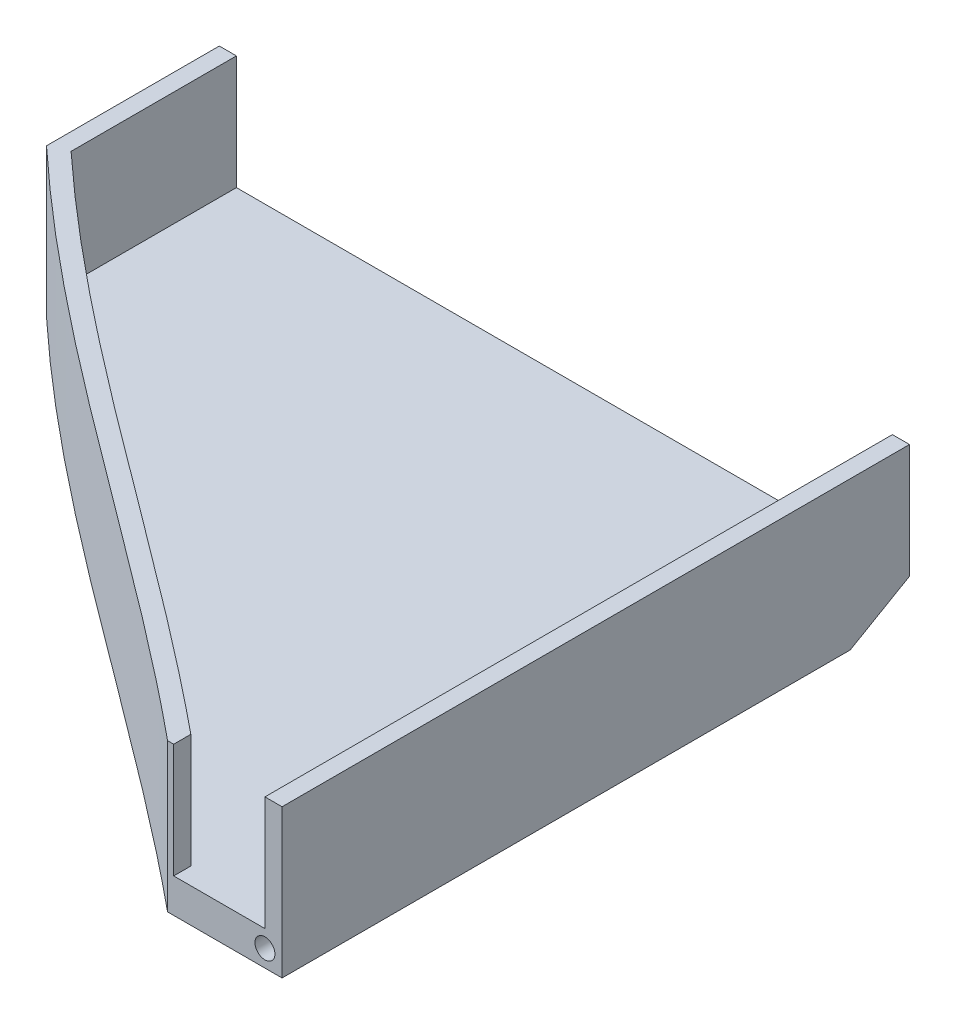
SolidWorks part; units mm, degrees
ref_plane "Front Plane" through (0, 0, 0) normal (0, 0, 1) x (1, 0, 0)
ref_plane "Top Plane" through (0, 0, 0) normal (0, 1, 0) x (1, 0, 0)
ref_plane "Right Plane" through (0, 0, 0) normal (1, 0, 0) x (0, 0, -1)
sketch "Sketch1" plane through (0, 0, 0) normal (0, 1, 0) x (1, 0, 0)
  line L0 (0, 0) -> (-121, 0)
  line L1 (0, 0) -> (0, -110)
  line L2 (-121, 0) -> (-121, -30.2986)
  line L3 (-20.07, -110) -> (0, -110)
  spline S0 degree 3 poles (-121, -30.2986) (-89.5585, -59.6551) (-53.1894, -82.7397) (-20.07, -110) knots 0 0 0 0 1 1 1 1
  point P6 (-121, -14.297)
  point P8 (-20.498, -110)
  dimension "D1" = 121
  dimension "D2" = 110
  dimension "D3" = 38.023
  dimension "D4" = 40
  dimension "D5" = 20.07
  dimension "D6" = 31.7014
  dimension "D7" = 30
  dimension "D8" = 18
extrude "Boss-Extrude1" add sketch "Sketch1" along normal blind 6
sketch "Sketch2" plane through (0, 0, 0) normal (0, 0, -1) x (-1, 0, 0)
  line L0 (3, 4.75) -> (3, 6) construction
  line L1 (0, 6) -> (121, 6) construction
  line L2 (3, 1.25) -> (3, 0) construction
  line L3 (0, 0) -> (121, 0) construction
  line L4 (1.25, 3) -> (0, 3) construction
  line L5 (0, 6) -> (0, 0) construction
  circle A0 centre (3, 3) radius 1.75
  dimension "D1" = 3.5
extrude "Cut-Extrude1" cut sketch "Sketch2" against normal through all both and the other way through all
sketch "Sketch3" plane through (0, 6, 0) normal (0, 1, 0) x (1, 0, 0)
  line L4 (-118, -3) -> (-118, 0)
  line L5 (0, 0) -> (-121, 0) construction
  line L6 (-3, -3) -> (-3, 0)
  line L7 (-18.9959, -107) -> (-18.9959, -110)
  line L8 (-3, -107) -> (-3, -3)
  line L9 (-3, -3) -> (-118, -3)
  line L10 (-118, -3) -> (-118, -28.9919)
  line L11 (-18.9959, -107) -> (-3, -107)
  line L12 (-3, -107) -> (-3, -3)
  line L14 (-118, -3) -> (-118, -28.9919)
  line L16 (-20.07, -110) -> (0, -110) construction
  line L17 (-3, -107) -> (-3, -110)
  line L18 (-118, 0) -> (-121, 0)
  line L19 (-3, -110) -> (0, -110)
  line L22 (0, -110) -> (0, 0)
  line L23 (0, 0) -> (-121, 0)
  line L24 (-121, 0) -> (-121, -30.2986)
  line L25 (-20.07, -110) -> (0, -110)
  line L26 (0, -110) -> (0, 0)
  line L27 (0, 0) -> (-3, 0)
  line L28 (-121, 0) -> (-121, -30.2986)
  line L29 (-20.07, -110) -> (-18.9959, -110)
  spline S2 degree 3 poles (649.1302, 1789.6761) (-350.2754, 298.2092) (-258.2349, 82.2153) (-85.8796, -56.0777) (-77.5136, -62.4365) (113.5898, -205.4544) (318.6219, -312.955) (-660.7218, -1970.0693) knots -4.756868 -4.756868 -4.756868 -4.756868 0.25 0.25 0.5 0.5 5.928718 5.928718 5.928718 5.928718 only from (-118, -28.9919) to (-18.9959, -107)
  spline S3 degree 3 poles (-118, -28.9919) (-110.2898, -36.1372) (-102.273, -42.9241) (-85.8796, -56.0777) (-77.5136, -62.4365) (-52.2742, -81.3252) (-35.2584, -93.6698) (-18.9959, -107) knots 0 0 0 0 0.25 0.25 0.5 0.5 1 1 1 1
  spline S4 degree 3 poles (571.5988, 1819.0788) (-1410.1109, -1437.193) (1283.6504, 1277.4641) (-683.5692, -1965.4922) knots -4.631393 -4.631393 -4.631393 -4.631393 5.820366 5.820366 5.820366 5.820366 only from (-121, -30.2986) to (-20.07, -110)
  spline S5 degree 3 poles (-121, -30.2986) (-89.5585, -59.6551) (-53.1894, -82.7397) (-20.07, -110) knots 0 0 0 0 1 1 1 1
  dimension "D2" = 0
  dimension "D1" = 3
extrude "Boss-Extrude2" add sketch "Sketch3" along normal blind 20
ref_plane "Plane1" through (0, 4.5, 2.5981) normal (0, -0.866, -0.5) x (-1, 0, 0)
sketch "Sketch4" plane through (0, 4.5, 2.5981) normal (0, -0.866, -0.5) x (-1, 0, 0)
  line L1 (-5.3255, 20.9869) -> (127.0112, 20.9869)
  line L2 (-5.3255, 20.9869) -> (-5.3255, -33.6963)
  line L3 (-5.3255, -33.6963) -> (127.0112, -33.6963)
  line L4 (127.0112, 20.9869) -> (127.0112, -33.6963)
extrude "Cut-Extrude2" cut sketch "Sketch4" along normal blind 20
